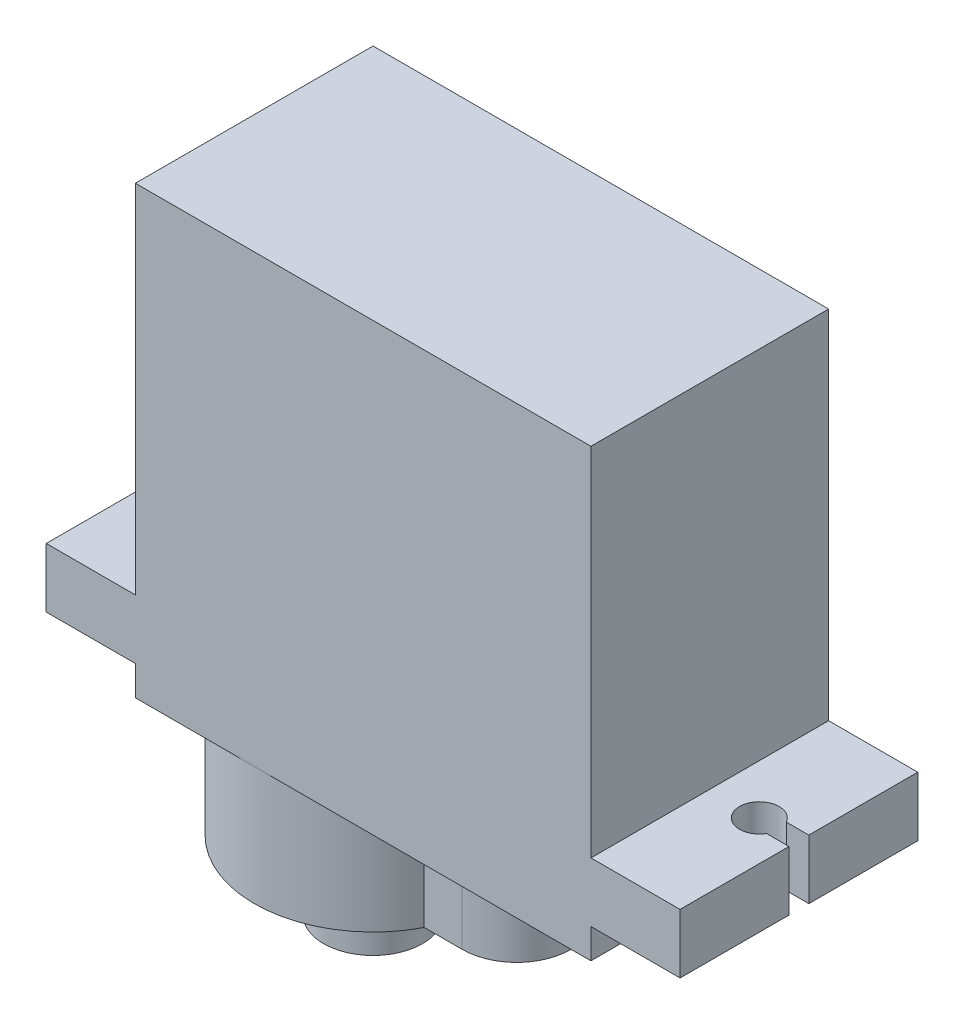
SolidWorks part; units mm, degrees
ref_plane "前视基准面" through (0, 0, 0) normal (0, 0, 1) x (1, 0, 0)
ref_plane "上视基准面" through (0, 0, 0) normal (0, 1, 0) x (1, 0, 0)
ref_plane "右视基准面" through (0, 0, 0) normal (1, 0, 0) x (0, 0, -1)
sketch "草图1" plane through (0, 0, 0) normal (0, 1, 0) x (1, 0, 0)
  line L1 (-11.5, -6) -> (11.5, -6)
  line L2 (-11.5, -6) -> (-11.5, 6)
  line L3 (-11.5, 6) -> (11.5, 6)
  line L4 (11.5, -6) -> (11.5, 6)
  line L5 (-11.5, -6) -> (11.5, 6) construction
  line L6 (-11.5, 6) -> (11.5, -6) construction
  point P0 (0, 0)
  dimension "D1" = 23
  dimension "D2" = 12
extrude "凸台-拉伸1" add sketch "草图1" along normal blind 22.5
ref_plane "基准面1" through (0, 4.5, 0) normal (0, 1, 0) x (1, 0, 0)
sketch "草图3" plane through (0, 4.5, 0) normal (0, 1, 0) x (1, 0, 0)
  line L0 (11.5, 6) -> (-11.5, 6) construction
  line L1 (-16, -6) -> (16, -6)
  line L2 (-16, -6) -> (-16, 6)
  line L3 (-16, 6) -> (16, 6)
  line L4 (16, -6) -> (16, 6)
  line L5 (-16, -6) -> (16, 6) construction
  line L6 (-16, 6) -> (16, -6) construction
  point P0 (0, 0)
  dimension "D1" = 32
extrude "凸台-拉伸2" add sketch "草图3" against normal blind 3
sketch "草图4" plane through (0, 1.5, 0) normal (0, -1, 0) x (1, 0, 0)
  line L0 (-16, -6) -> (-16, 6) construction
  line L1 (-16.941, 0.5) -> (-14.866, 0.5)
  line L2 (-14, 0) -> (-17.4, 0) construction
  line L3 (-16.941, -0.5) -> (-14.866, -0.5)
  line L4 (-16.941, 0.5) -> (-16.941, -0.5)
  line L5 (0, 0) -> (0, 10.2396) construction
  line L6 (14, 0) -> (17.4, 0) construction
  line L7 (16.941, 0.5) -> (16.941, -0.5)
  line L8 (16.941, -0.5) -> (14.866, -0.5)
  line L9 (16.941, 0.5) -> (14.866, 0.5)
  arc A0 (-14.866, -0.5) -> (-14.866, 0.5) centre (-14, 0) ccw
  arc A1 (14.866, -0.5) -> (14.866, 0.5) centre (14, 0) cw
  dimension "D1" = 2
  dimension "D2" = 2
  dimension "D3" = 1
extrude "切除-拉伸1" cut sketch "草图4" against normal blind 3
sketch "草图5" plane through (0, 0, 0) normal (0, -1, 0) x (1, 0, 0)
  line L0 (-11.5, 6) -> (-11.5, -6) construction
  line L1 (11.5, 6) -> (11.5, -6) construction
  circle A0 centre (-5.5, 0) radius 6
  dimension "D1" = 12
  dimension "D2" = 6
  dimension "D3" = 17
extrude "凸台-拉伸3" add sketch "草图5" along normal blind 6
sketch "草图6" plane through (0, -6, 0) normal (0, -1, 0) x (1, 0, 0)
  circle A0 centre (-5.5, 0) radius 2.5
  dimension "D1" = 5
extrude "凸台-拉伸4" add sketch "草图6" along normal blind 3.5
sketch "草图7" plane through (0, 0, 0) normal (0, 1, 0) x (1, 0, 0)
  line L0 (11.5, -6) -> (11.5, 6) construction
  line L1 (1.75, -2.75) -> (-1.6705, -2.75)
  line L2 (1.75, 2.75) -> (-1.6705, 2.75)
  line L3 (-1.6705, 2.75) -> (-1.6705, -2.75)
  arc A0 (1.75, -2.75) -> (1.75, 2.75) centre (1.75, 0) ccw
  point P4 (4.5, 0)
  dimension "D1" = 5.5
  dimension "D2" = 7
extrude "凸台-拉伸5" add sketch "草图7" against normal blind 6
sketch "草图8" plane through (-11.5, 0, 0) normal (-1, 0, 0) x (0, 0, 1)
  line L0 (-6, 22.5) -> (6, 22.5) construction
  line L1 (-1.5, 18.3) -> (1.5, 18.3)
  line L2 (-1.5, 18.3) -> (-1.5, 17.5)
  line L3 (-1.5, 17.5) -> (1.5, 17.5)
  line L4 (1.5, 18.3) -> (1.5, 17.5)
  point P6 (0, 17.5)
  dimension "D1" = 3
  dimension "D2" = 0.8
  dimension "D3" = 5
extrude "凸台-拉伸6" add sketch "草图8" along normal blind 1
